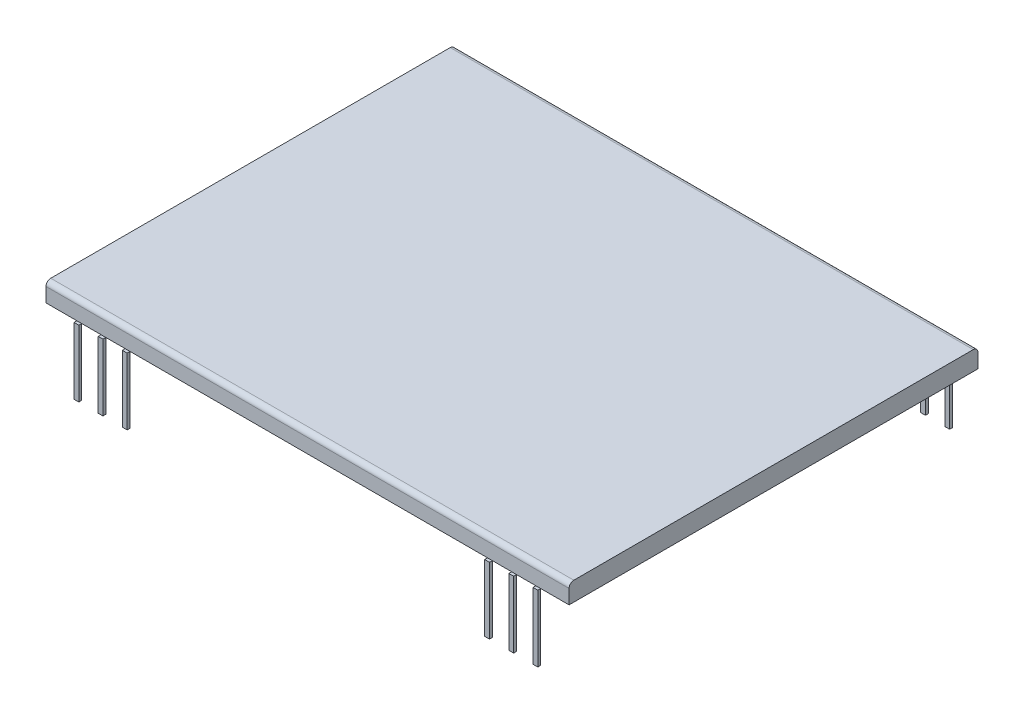
SolidWorks part; units mm, degrees
material "Plastique personnalisé"
ref_plane "Plan de face" through (0, 0, 0) normal (0, 0, 1) x (1, 0, 0)
ref_plane "Plan de dessus" through (0, 0, 0) normal (0, 1, 0) x (1, 0, 0)
ref_plane "Plan de droite" through (0, 0, 0) normal (1, 0, 0) x (0, 0, -1)
sketch "Esquisse1" plane through (0, 0, 0) normal (0, 1, 0) x (1, 0, 0)
  line L1 (-27.5, -21.5) -> (27.5, -21.5)
  line L2 (-27.5, -21.5) -> (-27.5, 21.5)
  line L3 (-27.5, 21.5) -> (27.5, 21.5)
  line L4 (27.5, -21.5) -> (27.5, 21.5)
  line L5 (-27.5, -21.5) -> (27.5, 21.5) construction
  line L6 (-27.5, 21.5) -> (27.5, -21.5) construction
  point P0 (0, 0)
  dimension "D1" = 55
  dimension "D2" = 43
extrude "Boss.-Extru.1" add sketch "Esquisse1" along normal blind 2
fillet "Congé1" radius 0.5 2 edges at (0, 2, -21.5) (0, 2, 21.5)
sketch "Esquisse2" plane through (0, 0, 0) normal (0, 1, 0) x (1, 0, 0)
  line L0 (-27.5, -21.5) -> (-24, -21.5) construction
  line L1 (27.5, -21.5) -> (-27.5, -21.5) construction
  line L2 (-24, -21.5) -> (-24.2495, -21.5) construction
  line L4 (-24.2495, -21.5) -> (-23.7495, -21.5)
  line L5 (-24.2495, -21.5) -> (-24.2495, -21.8)
  line L6 (-24.2495, -21.8) -> (-23.7495, -21.8)
  line L7 (-23.7495, -21.5) -> (-23.7495, -21.8)
  dimension "D1" = 3.5
  dimension "D2" = 0.5
  dimension "D3" = 0.3
extrude "Boss.-Extru.2" add sketch "Esquisse2" against normal blind 7 separate body
sketch "Esquisse3" plane through (0, 0, 0) normal (0, 1, 0) x (1, 0, 0)
  line L0 (-24.2495, -21.5) -> (-22.7152, -21.5)
pattern_linear "Répétition linéaire1" count 3 spacing 2.54 along (1, 0, 0) of "Boss.-Extru.2"
sketch "Esquisse4" plane through (0, 0, 0) normal (0, 1, 0) x (1, 0, 0)
  line L0 (-24.2495, -21.5) -> (-24.2495, 21.5) construction
  line L1 (-27.5, 21.5) -> (27.5, 21.5) construction
  line L3 (-24.2495, 21.5) -> (-23.7451, 21.5)
  line L4 (-24.2495, 21.5) -> (-24.2495, 21.8023)
  line L5 (-24.2495, 21.8023) -> (-23.7451, 21.8023)
  line L6 (-23.7451, 21.5) -> (-23.7451, 21.8023)
sketch "Esquisse5" plane through (0, 0, 0) normal (0, 1, 0) x (1, 0, 0)
  line L0 (-24.2495, 21.5) -> (-23.2019, 21.5)
  line L1 (-27.5, 21.5) -> (27.5, 21.5) construction
extrude "Boss.-Extru.3" add sketch "Esquisse4" against normal blind 7 separate body
pattern_linear "Répétition linéaire2" count 20 spacing 2.54 along (1, 0, 0) of "Boss.-Extru.3"
sketch "Esquisse6" plane through (0, 0, 0) normal (0, 1, 0) x (1, 0, 0)
  line L0 (24.5149, 21.5) -> (24.5149, -21.5) construction
  line L1 (27.5, -21.5) -> (-27.5, -21.5) construction
  line L3 (24.5149, -21.5) -> (24.01, -21.5)
  line L4 (24.5149, -21.5) -> (24.5149, -21.8)
  line L5 (24.5149, -21.8) -> (24.01, -21.8)
  line L6 (24.01, -21.5) -> (24.01, -21.8)
sketch "Esquisse7" plane through (0, 0, 0) normal (0, 1, 0) x (1, 0, 0)
  line L0 (24.01, -21.5) -> (22.965, -21.5)
  line L1 (27.5, -21.5) -> (-27.5, -21.5) construction
extrude "Boss.-Extru.4" add sketch "Esquisse6" against normal blind 7 separate body
pattern_linear "Répétition linéaire3" count 3 spacing 2.54 along (-1, 0, 0) of "Boss.-Extru.4"
